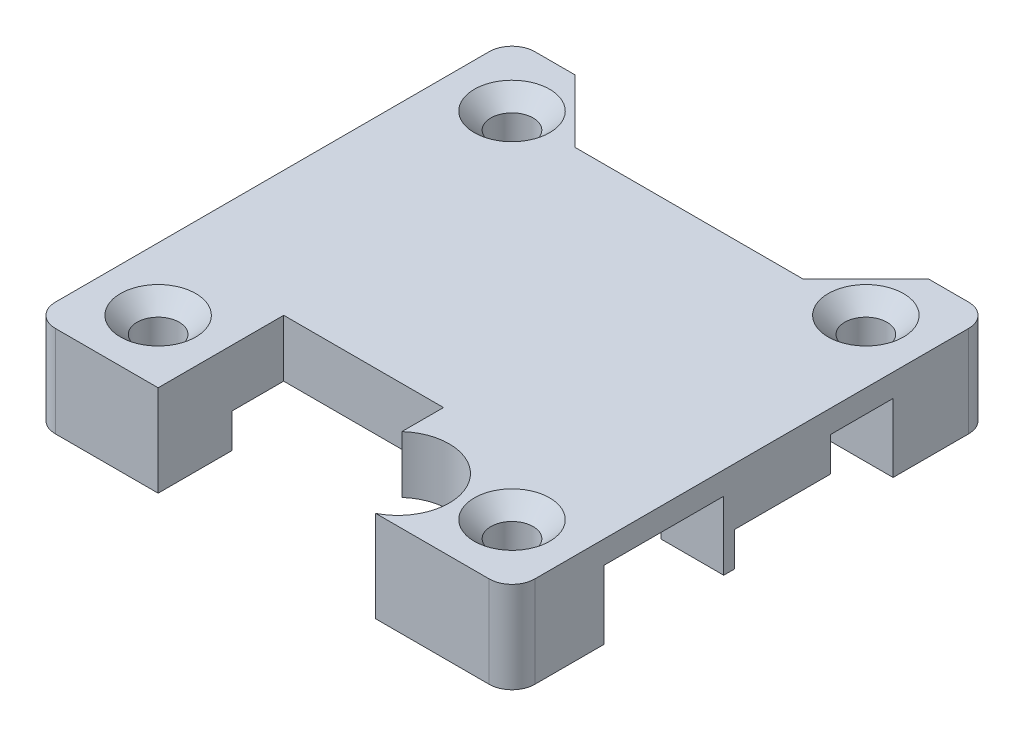
SolidWorks part; units mm, degrees
ref_plane "前视基准面" through (0, 0, 0) normal (0, 0, 1) x (1, 0, 0)
ref_plane "上视基准面" through (0, 0, 0) normal (0, 1, 0) x (1, 0, 0)
ref_plane "右视基准面" through (0, 0, 0) normal (1, 0, 0) x (0, 0, -1)
sketch "草图1" plane through (0, 0, 0) normal (0, 1, 0) x (1, 0, 0)
  line L1 (-21, -21) -> (21, -21)
  line L2 (-21, -21) -> (-21, 21)
  line L3 (-21, 21) -> (21, 21)
  line L4 (21, -21) -> (21, 21)
  line L5 (-21, -21) -> (21, 21) construction
  line L6 (-21, 21) -> (21, -21) construction
  line L7 (-15.5, -15.5) -> (15.5, -15.5) construction
  line L8 (-15.5, -15.5) -> (-15.5, 15.5) construction
  line L9 (-15.5, 15.5) -> (15.5, 15.5) construction
  line L10 (15.5, -15.5) -> (15.5, 15.5) construction
  line L11 (-15.5, -15.5) -> (15.5, 15.5) construction
  line L12 (-15.5, 15.5) -> (15.5, -15.5) construction
  circle A0 centre (15.5, 15.5) radius 1.85
  circle A1 centre (-15.5, 15.5) radius 1.85
  circle A2 centre (-15.5, -15.5) radius 1.85
  circle A3 centre (15.5, -15.5) radius 1.85
  point P0 (0, 0)
  point P6 (0, 0)
  dimension "D3" = 3.7
  dimension "D1" = 42
  dimension "D2" = 31
extrude "凸台-拉伸1" add sketch "草图1" along normal blind 8
fillet "圆角2" radius 2 1 edges at (-21, 4, -21)
fillet "圆角3" radius 2 1 edges at (-21, 4, 21)
fillet "圆角4" radius 2 1 edges at (21, 4, 21)
fillet "圆角5" radius 2 1 edges at (21, 4, -21)
sketch "草图2" plane through (0, 0, 0) normal (0, -1, 0) x (1, 0, 0)
  line L0 (21, 19) -> (21, -19) construction
  line L1 (21, 12.95) -> (15, 12.95)
  line L2 (21, 12.95) -> (21, 2.45)
  line L3 (21, 2.45) -> (15, 2.45)
  line L4 (15, 12.95) -> (15, 2.45)
  line L5 (-21, -19) -> (-21, 19) construction
  line L6 (-19, 21) -> (19, 21) construction
  line L7 (-21, 12.77) -> (-17, 12.77)
  line L8 (-21, 12.77) -> (-21, -13.23)
  line L9 (-21, -13.23) -> (-17, -13.23)
  line L10 (-17, 12.77) -> (-17, -13.23)
  line L11 (19, -21) -> (-19, -21) construction
  line L12 (21, -12.385) -> (8, -12.385)
  line L13 (21, -12.385) -> (21, -6.885)
  line L14 (21, -6.885) -> (8, -6.885)
  line L15 (8, -12.385) -> (8, -6.885)
  point P6 (21, 7.7)
  point P15 (-21, -0.23)
  point P20 (21, -9.635)
  dimension "D1" = 13.3
  dimension "D2" = 6
  dimension "D3" = 10.5
  dimension "D4" = 21.23
  dimension "D5" = 26
  dimension "D6" = 4
  dimension "D7" = 13
  dimension "D8" = 5.5
  dimension "D9" = 11.365
extrude "切除-拉伸1" cut sketch "草图2" against normal blind 6
sketch "草图3" plane through (0, 0, 0) normal (0, -1, 0) x (1, 0, 0)
  line L0 (21, 2.45) -> (21, -6.885) construction
  line L1 (21, -7.5) -> (15.442, -7.5)
  line L2 (21, -7.5) -> (21, 1.5)
  line L3 (21, 1.5) -> (15.442, 1.5)
  line L4 (15.442, -7.5) -> (15.442, 1.5)
  line L5 (19, -21) -> (-19, -21) construction
  point P6 (21, -3)
  dimension "D1" = 18
  dimension "D2" = 9
extrude "切除-拉伸2" cut sketch "草图3" against normal blind 3
sketch "草图5" plane through (0, 0, 0) normal (0, -1, 0) x (1, 0, 0)
  line L0 (-15.5, -21) -> (-10, -15.5)
  line L1 (19, -21) -> (-19, -21) construction
  line L2 (15.5, -21) -> (10, -15.5)
  line L3 (10, -15.5) -> (-10, -15.5)
  line L4 (-15.5, -21) -> (15.5, -21)
extrude "切除-拉伸3" cut sketch "草图5" against normal through all
sketch "草图10" plane through (0, 8, 0) normal (0, 1, 0) x (1, 0, 0)
  line L0 (21, -19) -> (21, 19) construction
  line L1 (-19, -21) -> (19, -21) construction
  line L2 (7, -21.5) -> (2.5, -21.5)
  line L3 (2.5, -21.5) -> (2.5, -17)
  arc A0 (7, -21.5) -> (2.5, -17) centre (7, -17) ccw
  dimension "D1" = 9
  dimension "D2" = 14
  dimension "D3" = 4
extrude "切除-拉伸13" cut sketch "草图10" against normal through all
sketch "草图6" plane through (0, 0, 0) normal (0, -1, 0) x (1, 0, 0)
  line L1 (-19, 21) -> (2.5, 21) construction
  line L2 (-10, 21) -> (4, 21)
  line L3 (-10, 21) -> (-10, 10)
  line L4 (-10, 10) -> (4, 10)
  line L6 (4, 21) -> (4, 10)
  line L7 (-21, 12.77) -> (-21, 19) construction
  line L8 (21, 19) -> (21, 12.95) construction
  dimension "D1" = 11
  dimension "D2" = 17
  dimension "D3" = 11
extrude "切除-拉伸4" cut sketch "草图6" against normal through all
sketch "草图7" plane through (0, 0, 0) normal (0, -1, 0) x (1, 0, 0)
  line L0 (-9.0163, 15.5) -> (-15.5, 9.0163)
  line L1 (-15.5, 15.5) -> (15.5, 15.5) construction
  line L2 (-15.5, 15.5) -> (-15.5, -15.5) construction
  line L3 (-15.5, -15.5) -> (15.5, -15.5) construction
  line L4 (15.5, 15.5) -> (15.5, -15.5) construction
  line L5 (-15.5, 9.0163) -> (-15.5, -9.0163)
  line L6 (-15.5, -9.0163) -> (-9.0163, -15.5)
  line L7 (-9.0163, -15.5) -> (9.0163, -15.5)
  line L8 (9.0163, -15.5) -> (15.5, -9.0163)
  line L9 (15.5, -9.0163) -> (15.5, 9.0163)
  line L10 (15.5, 9.0163) -> (9.0163, 15.5)
  line L11 (9.0163, 15.5) -> (-9.0163, 15.5)
extrude "切除-拉伸5" cut sketch "草图7" against normal blind 3
sketch "草图8" plane through (0, 8, 0) normal (0, 1, 0) x (1, 0, 0)
  line L0 (-21, 19) -> (-21, -19) construction
  line L1 (-8.5, -11) -> (2.5, -11) construction
  line L2 (-8.5, -11) -> (-8.5, -12) construction
  line L3 (-8.5, -12) -> (2.5, -12) construction
  line L4 (2.5, -11) -> (2.5, -12) construction
  line L5 (-19, -21) -> (-10, -21) construction
  line L6 (-3, -12) -> (-3, -11) construction
  circle A0 centre (-14.65, -11) radius 1
  circle A1 centre (8.65, -11) radius 1
  circle A2 centre (-14.65, 12.8) radius 1
  circle A3 centre (8.65, 12.8) radius 1
  point P4 (-3, -11)
  point P7 (-8.5, -11.5)
  dimension "D4" = 2
  dimension "D5" = 23.3
  dimension "D6" = 23.8
  dimension "D1" = 18
  dimension "D2" = 9.5
  dimension "D3" = 11
  dimension "D7" = 1
extrude "切除-拉伸6" [suppressed] cut sketch "草图8" against normal through all
hole_wizard "打孔尺寸(%根据十字)槽半沉头木螺钉的类型2" positions "草图21" profile "草图22" size "M3" standard "GB" slot yes end condition up to next
sketch "草图21" plane through (0, 8, 0) normal (0, 1, 0) x (1, 0, 0)
  point P0 (15.5, -15.5)
  point P3 (-15.5, -15.5)
  point P6 (-15.5, 15.5)
  point P9 (15.5, 15.5)
sketch "草图22" plane through (15.5, 8, 15.5) normal (1, 0, 0) x (0, 0, 1)
  line L0 (0, 0) -> (0, 8)
  line L1 (0, 8) -> (1.8, 8)
  line L2 (1.8, 8) -> (1.8, 1.5)
  line L3 (1.8, 1.5) -> (3.3, 0)
  line L5 (3.3, 0) -> (0, 0)
  line L6 (-1.8, 1.5) -> (-3.3, 0) construction
  line L11 (0, -6.35) -> (0, 107.95) construction
  dimension "通孔孔直径" = 3.6
  dimension "通孔孔深度" = 8
  dimension "近端锥形沉头孔直径" = 6.6
  dimension "近端锥形沉头孔角度" = 90
